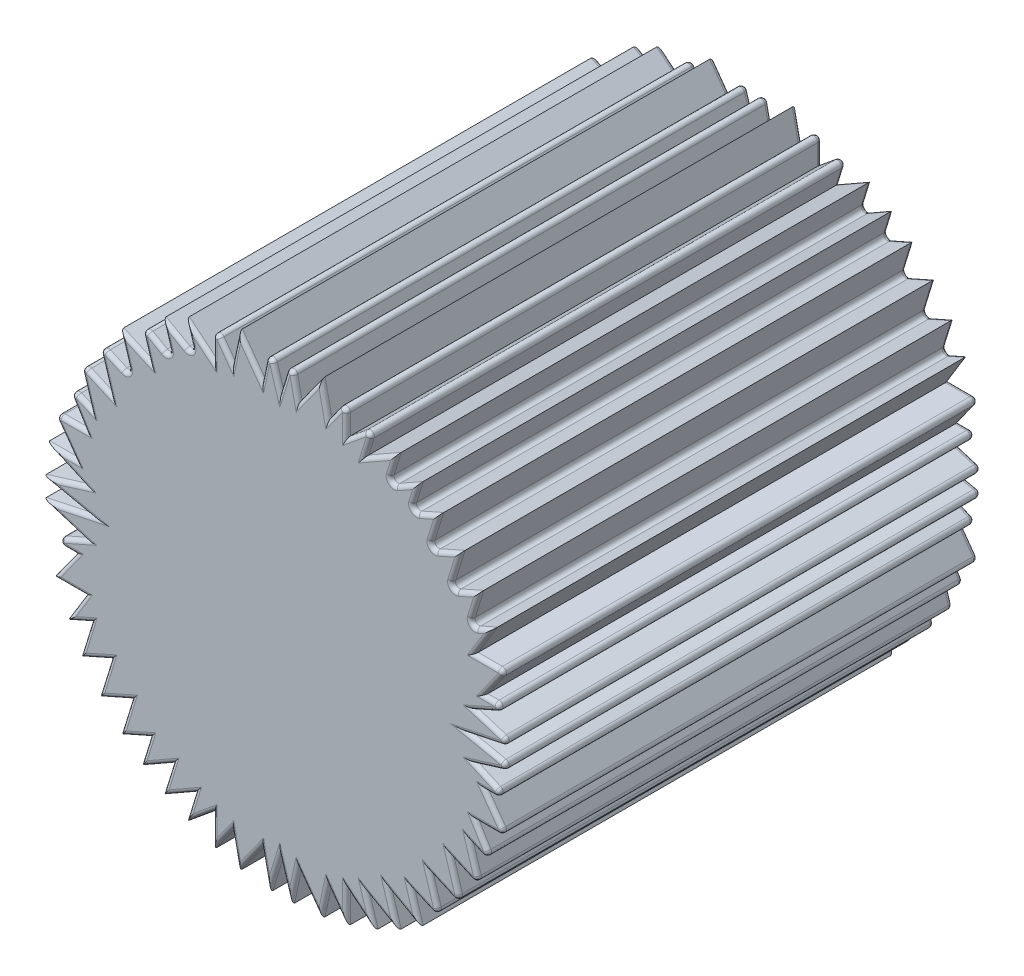
SolidWorks part; units mm, degrees
ref_plane "Front Plane" through (0, 0, 0) normal (0, 0, 1) x (1, 0, 0)
ref_plane "Top Plane" through (0, 0, 0) normal (0, 1, 0) x (1, 0, 0)
ref_plane "Right Plane" through (0, 0, 0) normal (1, 0, 0) x (0, 0, -1)
sketch "Sketch1" plane through (0, 0, 0) normal (0, 0, 1) x (1, 0, 0)
  line L0 (0, 0) -> (0, 50000) construction
  line L1 (0, 0) -> (-50000, 0) construction
  line L2 (0, 2.5509) -> (0.1374, 2.9969)
  line L3 (0.1374, 2.9969) -> (0.2314, 2.5509)
  line L4 (0.2314, 2.5509) -> (0.5221, 2.9542)
  line L5 (0.5221, 2.9542) -> (0.6071, 2.5509)
  line L6 (0.6071, 2.5509) -> (0.8436, 2.8789)
  line L7 (0.8436, 2.8789) -> (0.8436, 2.4665)
  line L8 (0.8436, 2.4665) -> (1.1915, 2.7533)
  line L9 (1.1915, 2.7533) -> (1.0743, 2.3731)
  line L10 (1.0743, 2.3731) -> (1.4842, 2.6071)
  line L11 (1.4842, 2.6071) -> (1.3579, 2.1971)
  line L12 (1.3579, 2.1971) -> (1.7621, 2.428)
  line L13 (1.7621, 2.428) -> (1.646, 2.0512)
  line L14 (1.646, 2.0512) -> (2.0207, 2.2174)
  line L15 (2.0207, 2.2174) -> (1.8783, 1.7552)
  line L16 (1.8783, 1.7552) -> (2.2901, 1.9379)
  line L17 (2.2901, 1.9379) -> (2.1386, 1.4462)
  line L18 (2.1386, 1.4462) -> (2.5262, 1.6182)
  line L19 (2.5262, 1.6182) -> (2.3866, 1.165)
  line L20 (2.3866, 1.165) -> (2.7014, 1.3047)
  line L21 (2.7014, 1.3047) -> (2.4564, 0.905)
  line L22 (2.4564, 0.905) -> (2.8603, 0.905)
  line L23 (2.8603, 0.905) -> (2.5789, 0.5147)
  line L24 (2.5789, 0.5147) -> (2.9555, 0.5147)
  line L25 (2.9555, 0.5147) -> (2.4564, 0.2933)
  line L26 (2.4564, 0.2933) -> (2.9973, 0.1266)
  line L27 (2.9973, 0.1266) -> (2.3965, 0)
  line L28 (1.646, -2.0512) -> (2.0207, -2.2174)
  line L29 (0, -2.5509) -> (0.1374, -2.9969)
  line L30 (0.1374, -2.9969) -> (0.2314, -2.5509)
  line L31 (0.2314, -2.5509) -> (0.5221, -2.9542)
  line L32 (0.5221, -2.9542) -> (0.6071, -2.5509)
  line L33 (0.6071, -2.5509) -> (0.8436, -2.8789)
  line L34 (0.8436, -2.4665) -> (1.1915, -2.7533)
  line L35 (0.8436, -2.8789) -> (0.8436, -2.4665)
  line L36 (1.1915, -2.7533) -> (1.0743, -2.3731)
  line L37 (1.0743, -2.3731) -> (1.4842, -2.6071)
  line L38 (1.4842, -2.6071) -> (1.3579, -2.1971)
  line L39 (1.3579, -2.1971) -> (1.7621, -2.428)
  line L40 (1.7621, -2.428) -> (1.646, -2.0512)
  line L41 (2.0207, -2.2174) -> (1.8783, -1.7552)
  line L42 (1.8783, -1.7552) -> (2.2901, -1.9379)
  line L43 (2.2901, -1.9379) -> (2.1386, -1.4462)
  line L44 (2.1386, -1.4462) -> (2.5262, -1.6182)
  line L45 (2.3866, -1.165) -> (2.7014, -1.3047)
  line L46 (2.5262, -1.6182) -> (2.3866, -1.165)
  line L47 (2.7014, -1.3047) -> (2.4564, -0.905)
  line L48 (2.4564, -0.905) -> (2.8603, -0.905)
  line L49 (2.8603, -0.905) -> (2.5789, -0.5147)
  line L50 (2.5789, -0.5147) -> (2.9555, -0.5147)
  line L51 (2.9555, -0.5147) -> (2.4564, -0.2933)
  line L52 (2.9973, -0.1266) -> (2.3965, 0)
  line L53 (2.4564, -0.2933) -> (2.9973, -0.1266)
  line L54 (-2.4564, -0.2933) -> (-2.9973, -0.1266)
  line L55 (-2.9973, -0.1266) -> (-2.3965, 0)
  line L56 (-2.9555, -0.5147) -> (-2.4564, -0.2933)
  line L57 (-2.5789, -0.5147) -> (-2.9555, -0.5147)
  line L58 (-2.8603, -0.905) -> (-2.5789, -0.5147)
  line L59 (-2.4564, -0.905) -> (-2.8603, -0.905)
  line L60 (-2.7014, -1.3047) -> (-2.4564, -0.905)
  line L61 (-2.5262, -1.6182) -> (-2.3866, -1.165)
  line L62 (-2.3866, -1.165) -> (-2.7014, -1.3047)
  line L63 (-2.1386, -1.4462) -> (-2.5262, -1.6182)
  line L64 (-2.2901, -1.9379) -> (-2.1386, -1.4462)
  line L65 (-1.8783, -1.7552) -> (-2.2901, -1.9379)
  line L66 (-2.0207, -2.2174) -> (-1.8783, -1.7552)
  line L67 (-1.7621, -2.428) -> (-1.646, -2.0512)
  line L68 (-1.3579, -2.1971) -> (-1.7621, -2.428)
  line L69 (-1.4842, -2.6071) -> (-1.3579, -2.1971)
  line L70 (-1.0743, -2.3731) -> (-1.4842, -2.6071)
  line L71 (-1.1915, -2.7533) -> (-1.0743, -2.3731)
  line L72 (-0.8436, -2.8789) -> (-0.8436, -2.4665)
  line L73 (-0.8436, -2.4665) -> (-1.1915, -2.7533)
  line L74 (-0.6071, -2.5509) -> (-0.8436, -2.8789)
  line L75 (-0.5221, -2.9542) -> (-0.6071, -2.5509)
  line L76 (-0.2314, -2.5509) -> (-0.5221, -2.9542)
  line L77 (-0.1374, -2.9969) -> (-0.2314, -2.5509)
  line L78 (0, -2.5509) -> (-0.1374, -2.9969)
  line L79 (-1.646, -2.0512) -> (-2.0207, -2.2174)
  line L80 (-2.9973, 0.1266) -> (-2.3965, 0)
  line L81 (-2.4564, 0.2933) -> (-2.9973, 0.1266)
  line L82 (-2.9555, 0.5147) -> (-2.4564, 0.2933)
  line L83 (-2.5789, 0.5147) -> (-2.9555, 0.5147)
  line L84 (-2.8603, 0.905) -> (-2.5789, 0.5147)
  line L85 (-2.4564, 0.905) -> (-2.8603, 0.905)
  line L86 (-2.7014, 1.3047) -> (-2.4564, 0.905)
  line L87 (-2.3866, 1.165) -> (-2.7014, 1.3047)
  line L88 (-2.5262, 1.6182) -> (-2.3866, 1.165)
  line L89 (-2.1386, 1.4462) -> (-2.5262, 1.6182)
  line L90 (-2.2901, 1.9379) -> (-2.1386, 1.4462)
  line L91 (-1.8783, 1.7552) -> (-2.2901, 1.9379)
  line L92 (-2.0207, 2.2174) -> (-1.8783, 1.7552)
  line L93 (-1.646, 2.0512) -> (-2.0207, 2.2174)
  line L94 (-1.7621, 2.428) -> (-1.646, 2.0512)
  line L95 (-1.3579, 2.1971) -> (-1.7621, 2.428)
  line L96 (-1.4842, 2.6071) -> (-1.3579, 2.1971)
  line L97 (-1.0743, 2.3731) -> (-1.4842, 2.6071)
  line L98 (-1.1915, 2.7533) -> (-1.0743, 2.3731)
  line L99 (-0.8436, 2.4665) -> (-1.1915, 2.7533)
  line L100 (-0.8436, 2.8789) -> (-0.8436, 2.4665)
  line L101 (-0.6071, 2.5509) -> (-0.8436, 2.8789)
  line L102 (-0.5221, 2.9542) -> (-0.6071, 2.5509)
  line L103 (-0.2314, 2.5509) -> (-0.5221, 2.9542)
  line L104 (-0.1374, 2.9969) -> (-0.2314, 2.5509)
  line L105 (0, 2.5509) -> (-0.1374, 2.9969)
  circle A0 centre (0, 0) radius 3
  point P33 (2.6969, 0.0633)
  point P35 (2.7672, 0.5147)
  point P59 (2.7672, -0.5147)
  point P63 (2.6969, -0.0633)
  point P115 (-2.6969, -0.0633)
  point P116 (-2.7672, -0.5147)
  dimension "D1" = 6
extrude "Boss-Extrude1" add sketch "Sketch1" along normal blind 6 contours L2 L105 L104 L103 L102 L101 L100 L99 L98 L97 L96 L95 L94 L93 L92 L91 L90 L89 L88 L87 L86 L85 L84 L83 L82 L81 L80 L55 L54 L56 L57 L58 L59 L60 L62 L61 L63 L64 L65 L66 L79 L67 L68 L69 L70 L71 L73 L72 L74 L75 L76
fillet "Fillet2" radius 0.05 80 edges at (0.8436, 2.6727, 6) (1.0175, 2.6099, 6) (2.3324, 1.5322, 6) (2.544, 1.2349, 6) (2.5789, 1.1048, 6) (2.7059, 0.404, 6) (2.6969, -0.0633, 6) (2.5789, -1.1048, 6) (2.3324, -1.5322, 6) (2.0842, -1.8466, 6) (1.9495, -1.9863, 6) (1.8334, -2.1343, 6) (1.7041, -2.2396, 6) (1.421, -2.4021, 6) (1.2793, -2.4901, 6) (0.8436, -2.6727, 6) (0.7254, -2.7149, 6) (-0.3768, -2.7526, 6) (-0.5646, -2.7526, 6) (-1.2793, -2.4901, 6) (-1.421, -2.4021, 6) (-1.9495, -1.9863, 6) (-2.4564, -1.3916, 6) (-2.7196, -0.7098, 6) (-2.7059, -0.404, 6) (-2.7672, 0.5147, 6) (-2.0842, 1.8466, 6) (-1.8334, 2.1343, 6) (-1.421, 2.4021, 6) (-1.1329, 2.5632, 6) (-1.0175, 2.6099, 6) (-0.5646, 2.7526, 6) (-0.3768, 2.7526, 6) (-0.0687, 2.7739, 6) (0.0687, 2.7739, 6) (-0.0687, 2.7739, 0) (-1.0175, 2.6099, 0) (-1.1329, 2.5632, 0) (-1.2793, 2.4901, 0) (-1.421, 2.4021, 0) (-2.0842, 1.8466, 0) (-2.4564, 1.3916, 0) (-2.544, 1.2349, 0) (-2.7672, 0.5147, 0) (-2.6969, -0.0633, 0) (-2.544, -1.2349, 0) (-1.9495, -1.9863, 0) (-1.8334, -2.1343, 0) (-1.421, -2.4021, 0) (-0.8436, -2.6727, 0) (-0.7254, -2.7149, 0) (0.7254, -2.7149, 0) (1.0175, -2.6099, 0) (1.421, -2.4021, 0) (1.56, -2.3125, 0) (2.2144, -1.6921, 0) (2.4564, -1.3916, 0) (2.6583, -0.905, 0) (2.7059, -0.404, 0) (2.7268, -0.2099, 0) (2.7268, 0.2099, 0) (2.4564, 1.3916, 0) (2.3324, 1.5322, 0) (1.8334, 2.1343, 0) (1.56, 2.3125, 0) (1.421, 2.4021, 0) (1.0175, 2.6099, 0) (0.5646, 2.7526, 0) (-2.2901, 1.9379, 3) (-2.7014, 1.3047, 3) (-1.0743, 2.3731, 3) (2.0207, -2.2174, 3) (2.7014, -1.3047, 3) (2.8603, -0.905, 3) (2.9973, -0.1266, 3) (2.9973, 0.1266, 3) (2.9555, 0.5147, 3) (2.1386, 1.4462, 3) (1.8783, 1.7552, 3) (1.3579, 2.1971, 3)
sketch "Sketch2" plane through (0, 0, 0) normal (0, 0, -1) x (-1, 0, 0)
  circle A0 centre (0, 0) radius 1
  dimension "D1" = 2
extrude "Cut-Extrude1" cut sketch "Sketch2" against normal blind 2
